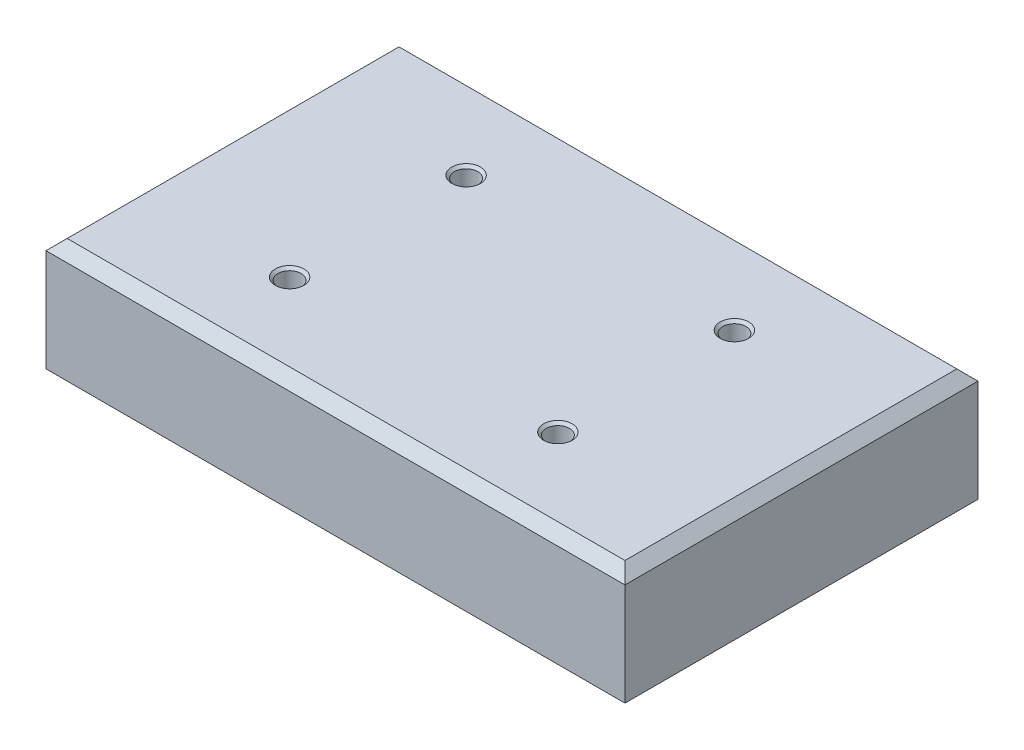
SolidWorks part; units mm, degrees
ref_plane "Front Plane" through (0, 0, 0) normal (0, 0, 1) x (1, 0, 0)
ref_plane "Top Plane" through (0, 0, 0) normal (0, 1, 0) x (1, 0, 0)
ref_plane "Right Plane" through (0, 0, 0) normal (1, 0, 0) x (0, 0, -1)
sketch "Sketch1" plane through (0, 0, 0) normal (0, 1, 0) x (1, 0, 0)
  line L1 (-41, 25) -> (41, 25)
  line L2 (-41, 25) -> (-41, -25)
  line L3 (-41, -25) -> (41, -25)
  line L4 (41, 25) -> (41, -25)
  line L5 (-41, 25) -> (41, -25) construction
  line L6 (-41, -25) -> (41, 25) construction
  point P0 (0, 0)
  dimension "D1" = 82
  dimension "D2" = 50
extrude "Boss-Extrude1" add sketch "Sketch1" along normal blind 16
hole_wizard "M4 Tapped Hole3" positions "Sketch5" profile "Sketch6" tap size "M4" standard "DIN"
sketch "Sketch5" plane through (0, 16, 0) normal (0, 1, 0) x (1, 0, 0)
  line L0 (0, 25) -> (0, 0) construction
  line L1 (41, 25) -> (-41, 25) construction
  line L2 (0, 0) -> (-41, 0) construction
  line L3 (-41, 25) -> (-41, -25) construction
  point P0 (-19, 12.5)
  point P2 (19, 12.5)
  point P4 (19, -12.5)
  point P6 (-19, -12.5)
  dimension "D1" = 38
  dimension "D2" = 25
sketch "Sketch6" plane through (-19, 16, -12.5) normal (1, 0, 0) x (0, 0, 1)
  line L0 (0, 0) -> (0, 8.9914)
  line L1 (0, 8.9914) -> (1.65, 8)
  line L2 (1.65, 8) -> (1.65, 0.375)
  line L3 (1.65, 0.375) -> (2.025, 0)
  line L5 (2.025, 0) -> (0, 0)
  line L6 (-1.65, 0.375) -> (-2.025, 0) construction
  line L10 (0, 8.9914) -> (-1.65, 8) construction
  line L11 (0, -6.35) -> (0, 107.95) construction
  dimension "Tap Drill Dia." = 3.3
  dimension "Tap Drill Depth" = 8
  dimension "Near C'Sink Dia." = 4.05
  dimension "Near C'Sink Angle" = 90
  dimension "Drill Angle" = 118
cosmetic thread "Hole Thread6" parameters "D1"=6, "D2"=4
cosmetic thread "Hole Thread7" parameters "D1"=6, "D2"=4
cosmetic thread "Hole Thread8" parameters "D1"=6, "D2"=4
cosmetic thread "Hole Thread9" parameters "D1"=6, "D2"=4
chamfer "Chamfer1" distance 1.5 angle 45 4 edges at (0, 16, -25) (41, 16, 0) (0, 16, 25) (-41, 16, 0)
sketch "Sketch7" plane through (0, 0, -25) normal (0, 0, -1) x (-1, 0, 0)
  text T0 "Designed by:\r\n                       Jagdish"
extrude "Boss-Extrude3" add sketch "Sketch7" along normal blind 1
equation "\"1.5.00mm\"=10"
